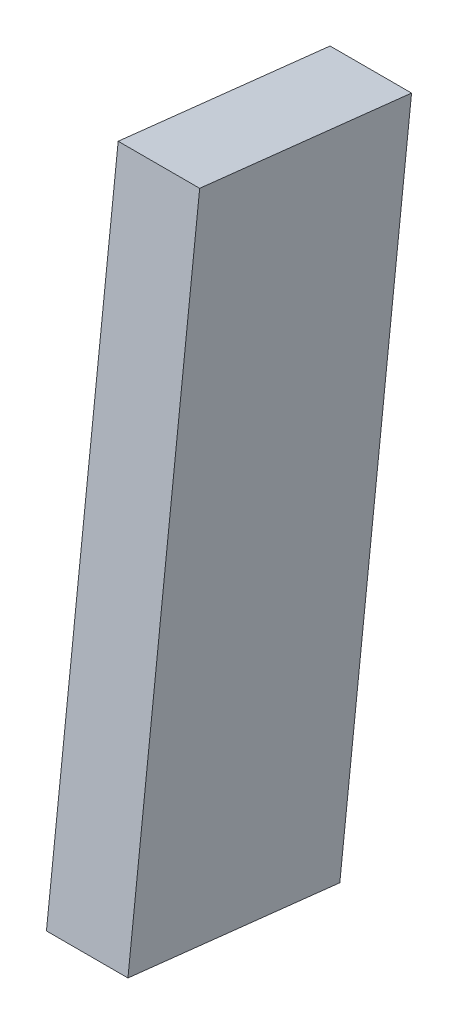
SolidWorks part; units mm, degrees
ref_plane "Front Plane" through (0, 0, 0) normal (0, 0, 1) x (1, 0, 0)
ref_plane "Top Plane" through (0, 0, 0) normal (0, 1, 0) x (1, 0, 0)
ref_plane "Right Plane" through (0, 0, 0) normal (1, 0, 0) x (0, 0, -1)
ref_plane "Plane1" through (-1564.6641, 0, 0) normal (1, 0, 0) x (0, 0, -1)
sketch "Sketch1" plane through (-1564.6641, 0, 0) normal (1, 0, 0) x (0, 0, -1)
  line L0 (-1161.0221, 412.819) -> (-1174.0221, 414.2582)
  line L2 (-1021.4153, 397.3639) -> (-1189.9051, 416.0165) construction
  line L3 (-1174.0221, 414.2582) -> (-1178.4234, 374.5011)
  line L4 (-1194.3064, 376.2594) -> (-996.4443, 354.3552) construction
  line L5 (-1161.0221, 412.819) -> (-1165.4234, 373.0619)
  line L6 (-1165.4234, 373.0619) -> (-1178.4234, 374.5011)
  dimension "D1" = 13
  dimension "D2" = 5.98
extrude "Boss-Extrude1" add sketch "Sketch1" along normal blind 5
